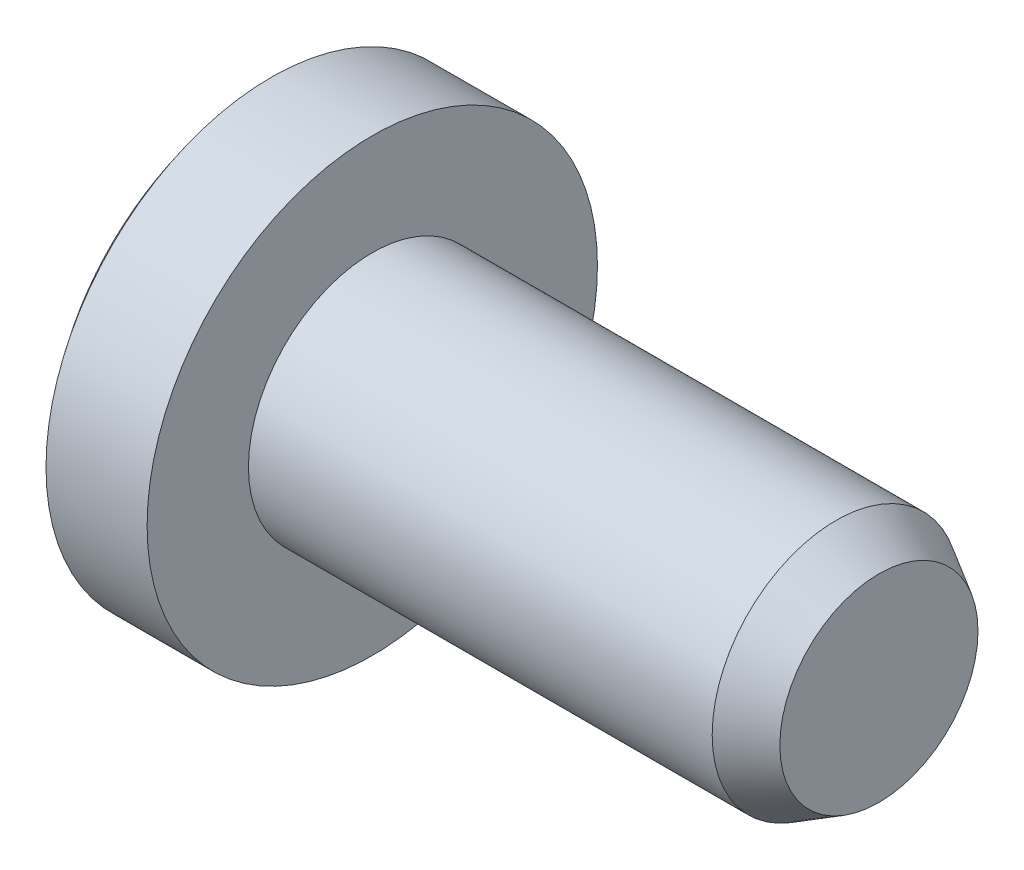
SolidWorks part; units mm, degrees
ref_plane "Front Plane" through (0, 0, 0) normal (0, 0, 1) x (1, 0, 0)
ref_plane "Top Plane" through (0, 0, 0) normal (0, 1, 0) x (1, 0, 0)
ref_plane "Right Plane" through (0, 0, 0) normal (1, 0, 0) x (0, 0, -1)
sketch "Sketch1" plane through (0, 0, 0) normal (0, 0, 1) x (1, 0, 0)
  line L0 (0, 0) -> (5.2282, 0) construction
  line L2 (0, 2) -> (-0.898, 2)
  line L3 (-1.6, 0) -> (-1.6, -0.7496) construction
  line L4 (-1.6, 0) -> (4.5, 0)
  line L5 (0, 1.1) -> (4.5, 1.1)
  line L6 (4.5, 1.1) -> (4.5, 0)
  line L7 (0, 1.1) -> (0, 2)
  arc A0 (-0.898, 2) -> (-1.6, 0) centre (1.6, 0) ccw
  dimension "rf" = 3.2
  dimension "Dk" = 4
  dimension "K" = 1.6
  dimension "d" = 2.2
  dimension "l" = 4.5
revolve "Revolve1" add sketch "Sketch1" angle 360 about L0
cosmetic thread "ThreadCosmetic" [suppressed] parameters "D1"=4.28, "D2"=1.65
chamfer "Chamfer1" distance 0.22 angle 60 1 edges at (4.5, 0, 1.1)
sketch "Sketch5" plane through (0, 0, 0) normal (0, 0, 1) x (1, 0, 0)
  line L0 (0.3703, 0.825) -> (0.2069, 0.825)
  line L1 (0.2069, 0.825) -> (0.0481, 1.1)
  line L2 (0.3703, 0.825) -> (0.529, 1.1)
  line L3 (0.0481, 1.1) -> (0.0481, 1.35)
  line L4 (0.529, 1.1) -> (0.529, 1.35)
  line L5 (0.0481, 1.35) -> (0.529, 1.35)
  line L6 (0.2886, 0.825) -> (0.2886, 0) construction
  line L7 (0, 0) -> (7.3035, 0) construction
  line L9 (4.1189, 1.1) -> (0, 1.1) construction
  line L12 (0, -1.1) -> (0, 1.1) construction
  dimension "D2" = 60
  dimension "D3" = 0.25
  dimension "advance" = 0.4809
  dimension "minordia" = 1.65
  dimension "threadstart" = 0.2886
revolve "ThreadSchematic" [suppressed] cut sketch "Sketch5" angle 360 about L7
pattern_linear "ThdSchPat" [suppressed] count 10 spacing 0.4809 along (1, 0, 0)
sketch "Sketch2" plane through (0, 0, 0) normal (0, 0, 1) x (1, 0, 0)
  line L0 (0, 0) -> (5.7679, 0) construction
  line L1 (4.5, 0) -> (2.5947, 1.1)
  line L3 (4.5, 1.1) -> (4.5, 0) construction
  line L4 (2.5947, 1.1) -> (2.5947, 1.2)
  line L5 (2.5947, 1.2) -> (4.6, 1.2)
  line L6 (4.6, 1.2) -> (4.6, 0)
  line L7 (4.6, 0) -> (4.5, 0)
  point P9 (0, 1.1)
  dimension "D1" = 30
  dimension "D2" = 0.1
  dimension "D3" = 0.1
revolve "EndCone" [suppressed] cut sketch "Sketch2" angle 360 about L0
ref_plane "Plane4" through (-1.6, 0, 0) normal (1, 0, 0) x (0, 0, -1)
sketch "Sketch3" plane through (-1.6, 0, 0) normal (1, 0, 0) x (0, 0, -1)
  line L0 (0, 2.343) -> (0, -2.4842) construction
  line L1 (2.7661, 0) -> (-3.4558, 0) construction
  line L2 (-0.2375, 0.95) -> (0.2375, 0.95)
  line L3 (0.2375, 0.95) -> (0.1425, 0.57)
  line L4 (0, 0) -> (1.9578, 1.9578) construction
  line L5 (0.1425, 0.57) -> (0.299, 0.299)
  line L6 (0.1425, 0.57) -> (0, 0) construction
  line L7 (-0.1425, 0.57) -> (-0.299, 0.299)
  line L8 (-0.2375, 0.95) -> (-0.1425, 0.57)
  line L9 (0.95, 0.2375) -> (0.95, -0.2375)
  line L10 (0.95, -0.2375) -> (0.57, -0.1425)
  line L11 (0.57, -0.1425) -> (0.299, -0.299)
  line L12 (0.57, 0.1425) -> (0.299, 0.299)
  line L13 (0.95, 0.2375) -> (0.57, 0.1425)
  line L14 (0.2375, -0.95) -> (-0.2375, -0.95)
  line L15 (-0.2375, -0.95) -> (-0.1425, -0.57)
  line L16 (-0.1425, -0.57) -> (-0.299, -0.299)
  line L17 (0.1425, -0.57) -> (0.299, -0.299)
  line L18 (0.2375, -0.95) -> (0.1425, -0.57)
  line L19 (-0.95, -0.2375) -> (-0.95, 0.2375)
  line L20 (-0.95, 0.2375) -> (-0.57, 0.1425)
  line L21 (-0.57, 0.1425) -> (-0.299, 0.299)
  line L22 (-0.57, -0.1425) -> (-0.299, -0.299)
  line L23 (-0.95, -0.2375) -> (-0.57, -0.1425)
  point P14 (0, 0.95)
  point P23 (0.95, 0)
  point P30 (0, -0.95)
  point P37 (-0.95, 0)
  dimension "D1" = 45
  dimension "m" = 1.9
  dimension "D3" = 0.475
  dimension "D4" = 75
  dimension "D5" = 1.14
extrude "Cut-Extrude1" cut sketch "Sketch3" along normal blind 0.8 draft 6
sketch "Sketch4" plane through (-1.6, 0, 0) normal (1, 0, 0) x (0, 0, -1)
  line L0 (0, 2.1951) -> (0, -2.1951) construction
  line L1 (2.1996, 0) -> (-2.3835, 0) construction
  line L2 (-0.8397, -0.8397) -> (0.8397, 0.8397) construction
  line L3 (0.95, 0.2375) -> (-0.95, 0.2375)
  line L4 (0.95, 0.2375) -> (0.95, -0.2375)
  line L5 (0.95, -0.2375) -> (-0.95, -0.2375)
  line L6 (-0.95, 0.2375) -> (-0.95, -0.2375)
  line L7 (0.2375, 0.95) -> (-0.2375, 0.95)
  line L8 (0.2375, 0.95) -> (0.2375, -0.95)
  line L9 (0.2375, -0.95) -> (-0.2375, -0.95)
  line L10 (-0.2375, 0.95) -> (-0.2375, -0.95)
  line L11 (0.8397, 0.8397) -> (0.3859, 0.2375)
  line L12 (0.8397, 0.8397) -> (0.2375, 0.3859)
  line L13 (0.2375, 0.3859) -> (-0.2375, 0.3859) construction
  line L14 (0, 0) -> (-0.8397, 0.8397) construction
  line L15 (-0.8397, -0.8397) -> (-0.2375, -0.3859)
  line L16 (-0.8397, -0.8397) -> (-0.3859, -0.2375)
  line L17 (-0.2375, 0.3859) -> (-0.8397, 0.8397)
  line L18 (-0.8397, 0.8397) -> (-0.3859, 0.2375)
  line L19 (-0.3859, -0.2375) -> (-0.3859, 0.2375) construction
  line L20 (0.3859, -0.2375) -> (0.8397, -0.8397)
  line L21 (0.8397, -0.8397) -> (0.2375, -0.3859)
  circle A0 centre (0, 0) radius 1.1875 construction
  dimension "m" = 1.9
  dimension "D1" = 2.375
  dimension "D2" = 0.475
  dimension "D3" = 45
  dimension "D4" = 8
  dimension "D5" = 45
extrude "TypeZ" [suppressed] cut sketch "Sketch4" along normal blind 0.8
equation "\"D1@Chamfer1\" = \"d@Sketch1\"/10"
equation "\"D1@ThreadCosmetic\" = \"l@Sketch1\" - \"D1@Chamfer1\""
equation "\"minordia@Sketch5\" = \"D2@ThreadCosmetic\""
equation "\"D1@Plane4\" = \"K@Sketch1\""
equation "\"D5@Sketch3\" = \"m@Sketch3\" * 3 / 5"
equation "\"D3@Sketch3\" = \"m@Sketch3\" / 4"
equation "\"D2@Sketch4\" =  \"m@Sketch4\" / 4"
equation "\"D1@TypeZ\" = \"K@Sketch1\" / 2"
equation "\"D1@Sketch4\" = \"m@Sketch4\" * 5 / 4"
equation "\"m@Sketch4\" = \"m@Sketch3\""
equation "\"threadstart@Sketch5\" = \"advance@Sketch5\"*0.6"
equation "\"D1@ThdSchPat\" = int((\"l@Sketch1\"/\"advance@Sketch5\") + 0.999)"
equation "\"D3@ThdSchPat\" = \"advance@Sketch5\""
